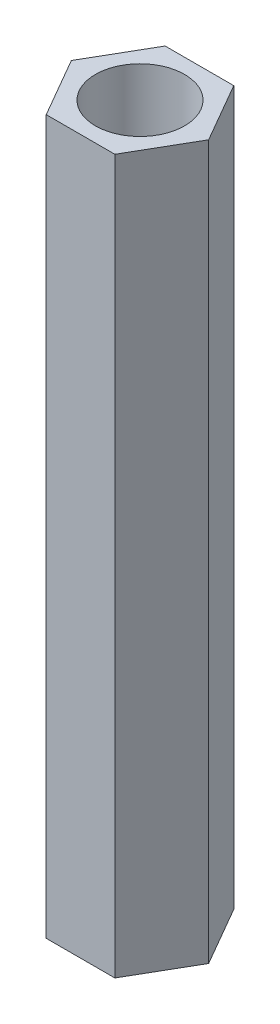
SolidWorks part; units mm, degrees
ref_plane "Front Plane" through (0, 0, 0) normal (0, 0, 1) x (1, 0, 0)
ref_plane "Top Plane" through (0, 0, 0) normal (0, 1, 0) x (1, 0, 0)
ref_plane "Right Plane" through (0, 0, 0) normal (1, 0, 0) x (0, 0, -1)
sketch "Sketch1" plane through (0, 0, 0) normal (0, 1, 0) x (1, 0, 0)
  line L1 (1.7321, -3) -> (3.4641, 0)
  line L2 (3.4641, 0) -> (1.7321, 3)
  line L3 (1.7321, 3) -> (-1.7321, 3)
  line L4 (-1.7321, 3) -> (-3.4641, 0)
  line L5 (-3.4641, 0) -> (-1.7321, -3)
  line L6 (-1.7321, -3) -> (1.7321, -3)
  circle A0 centre (0, 0) radius 3 construction
  circle A1 centre (0, 0) radius 2.25
  dimension "D1" = 4.5
  dimension "D2" = 6
extrude "Boss-Extrude1" add sketch "Sketch1" along normal blind 36
